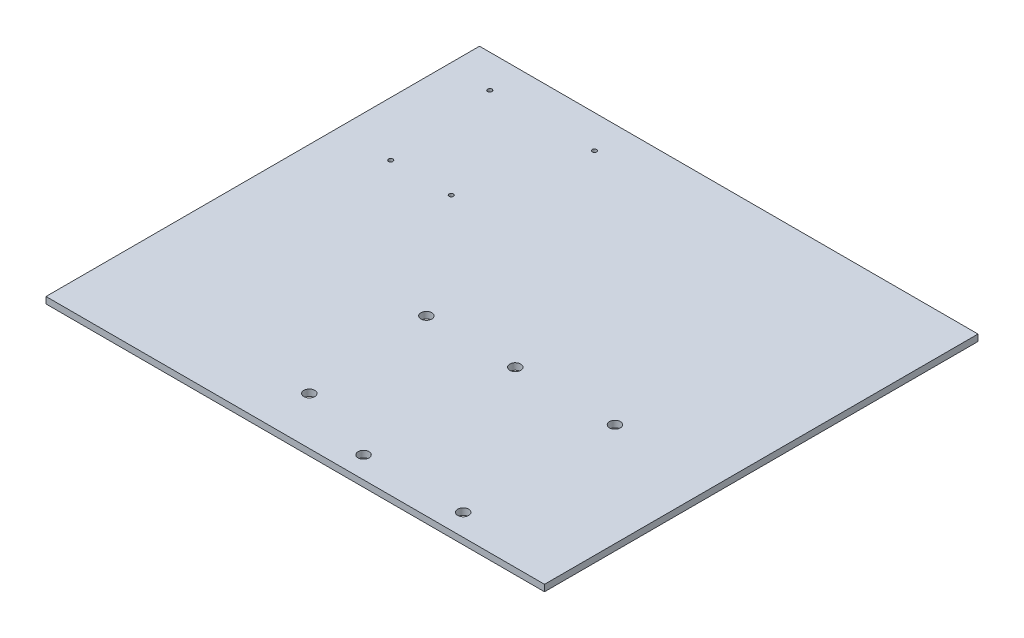
SolidWorks part; units mm, degrees
ref_plane "Front Plane" through (0, 0, 0) normal (0, 0, 1) x (1, 0, 0)
ref_plane "Top Plane" through (0, 0, 0) normal (0, 1, 0) x (1, 0, 0)
ref_plane "Right Plane" through (0, 0, 0) normal (1, 0, 0) x (0, 0, -1)
sketch "Sketch1" plane through (0, 0, 0) normal (0, 1, 0) x (1, 0, 0)
  line L0 (0, 84.6549) -> (0, -47.0744) construction
  line L1 (0, -47.0744) -> (0, 0) construction
  line L2 (0, 0) -> (45.8877, 0) construction
  line L3 (-93.5, 10) -> (0, 10) construction
  line L4 (-47.5, 10) -> (-47.5, 0) construction
  line L5 (-93.5, 0) -> (-93.5, 10) construction
  line L6 (0, 22) -> (-130.5, 22) construction
  line L7 (-130.5, 22) -> (-130.5, 0) construction
  line L8 (0, 80) -> (-134.5, 80) construction
  line L9 (-134.5, 80) -> (-134.5, 0) construction
  line L10 (-93.5, 10) -> (-93.5, 80) construction
  line L11 (-47.5, 10) -> (-47.5, 80) construction
  line L12 (-204.92, 200) -> (-204.92, 133.96) construction
  line L13 (0, 0) -> (-230, 0)
  line L14 (0, 0) -> (0, 200)
  line L15 (0, 200) -> (-230, 200)
  line L16 (-230, 0) -> (-230, 200)
  line L17 (-159.2, 200) -> (-159.2, 133.96) construction
  line L18 (-159.2, 133.96) -> (-204.92, 133.96) construction
  line L19 (-176.98, 133.96) -> (-176.98, 200) construction
  line L20 (-161.74, 184.76) -> (-161.74, 200) construction
  line L21 (-210, 184.76) -> (-210, 200) construction
  line L22 (-210, 184.76) -> (-161.74, 184.76) construction
  circle A0 centre (-130.5, 22) radius 2.525
  circle A2 centre (-93.5, 80) radius 2.525
  circle A3 centre (-134.5, 80) radius 2.525
  circle A4 centre (-47.5, 80) radius 2.525
  circle A5 centre (-47.5, 10) radius 2.525
  circle A6 centre (-93.5, 10) radius 2.525
  circle A11 centre (-210, 184.76) radius 1
  circle A12 centre (-161.74, 184.76) radius 1
  circle A13 centre (-176.98, 133.96) radius 1
  circle A14 centre (-204.92, 133.96) radius 1
  dimension "D8" = 5.05
  dimension "D9" = 5.05
  dimension "D10" = 5.05
  dimension "D11" = 5.05
  dimension "D12" = 5.05
  dimension "D13" = 5.05
  dimension "D26" = 2
  dimension "D27" = 2
  dimension "D28" = 2
  dimension "D29" = 2
  dimension "D2" = 47.5
  dimension "D1" = 10
  dimension "D3" = 93.5
  dimension "D4" = 22
  dimension "D5" = 130.5
  dimension "D6" = 80
  dimension "D7" = 134.5
  dimension "D14" = 230
  dimension "D15" = 200
  dimension "D16" = 66.04
  dimension "D17" = 17.78
  dimension "D18" = 45.72
  dimension "D19" = 2.54
  dimension "D20" = 50.8
  dimension "D21" = 15.24
  dimension "D30" = 20
extrude "Boss-Extrude2" add sketch "Sketch1" along normal blind 3
equation "\"Base thickness\"= 3mm"
equation "\"Arduino hole diameter\"= 2mm"
equation "\"D26@Sketch1\"=\"Arduino hole diameter\""
equation "\"D27@Sketch1\"=\"Arduino hole diameter\""
equation "\"D28@Sketch1\"=\"Arduino hole diameter\""
equation "\"D29@Sketch1\"=\"Arduino hole diameter\""
equation "\"D1@Boss-Extrude2\"=\"Base thickness\""
